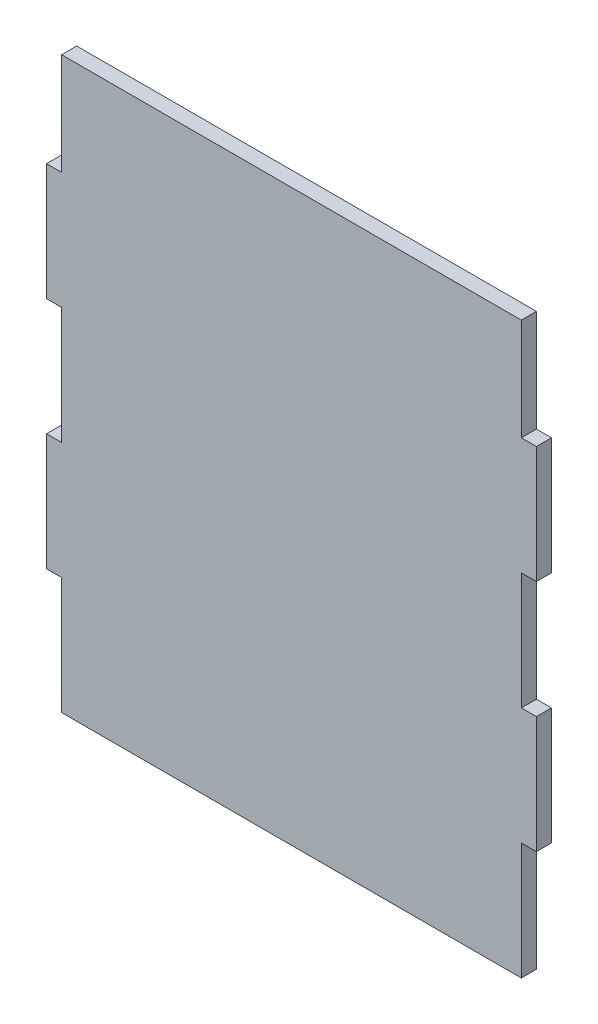
SolidWorks part; units mm, degrees
ref_plane "Front Plane" through (0, 0, 0) normal (0, 0, 1) x (1, 0, 0)
ref_plane "Top Plane" through (0, 0, 0) normal (0, 1, 0) x (1, 0, 0)
ref_plane "Right Plane" through (0, 0, 0) normal (1, 0, 0) x (0, 0, -1)
sketch "Sketch1" plane through (0, 0, 0) normal (0, 0, 1) x (1, 0, 0)
  line L1 (-81.825, 0) -> (15, 0)
  line L2 (-81.825, 0) -> (-81.825, 24.635)
  line L13 (-81.825, 120) -> (15, 120)
  line L24 (15, 120) -> (15, 98.54)
  line L25 (15, 98.54) -> (18.175, 98.54)
  line L26 (18.175, 98.54) -> (18.175, 73.905)
  line L27 (18.175, 73.905) -> (15, 73.905)
  line L28 (15, 73.905) -> (15, 49.27)
  line L29 (15, 49.27) -> (18.175, 49.27)
  line L30 (18.175, 49.27) -> (18.175, 24.635)
  line L31 (18.175, 24.635) -> (15, 24.635)
  line L32 (15, 24.635) -> (15, 0)
  line L33 (-33.4125, 0) -> (-33.4125, 120) construction
  line L34 (-81.825, 98.54) -> (-85, 98.54)
  line L35 (-85, 98.54) -> (-85, 73.905)
  line L36 (-85, 73.905) -> (-81.825, 73.905)
  line L37 (-81.825, 49.27) -> (-85, 49.27)
  line L38 (-85, 49.27) -> (-85, 24.635)
  line L39 (-85, 24.635) -> (-81.825, 24.635)
  line L40 (-81.825, 49.27) -> (-81.825, 73.905)
  line L41 (-81.825, 98.54) -> (-81.825, 120)
  dimension "D1" = 120
  dimension "D2" = 21.46
  dimension "D3" = 3.175
  dimension "D4" = 96.825
extrude "Boss-Extrude1" add sketch "Sketch1" along normal blind 3.175
